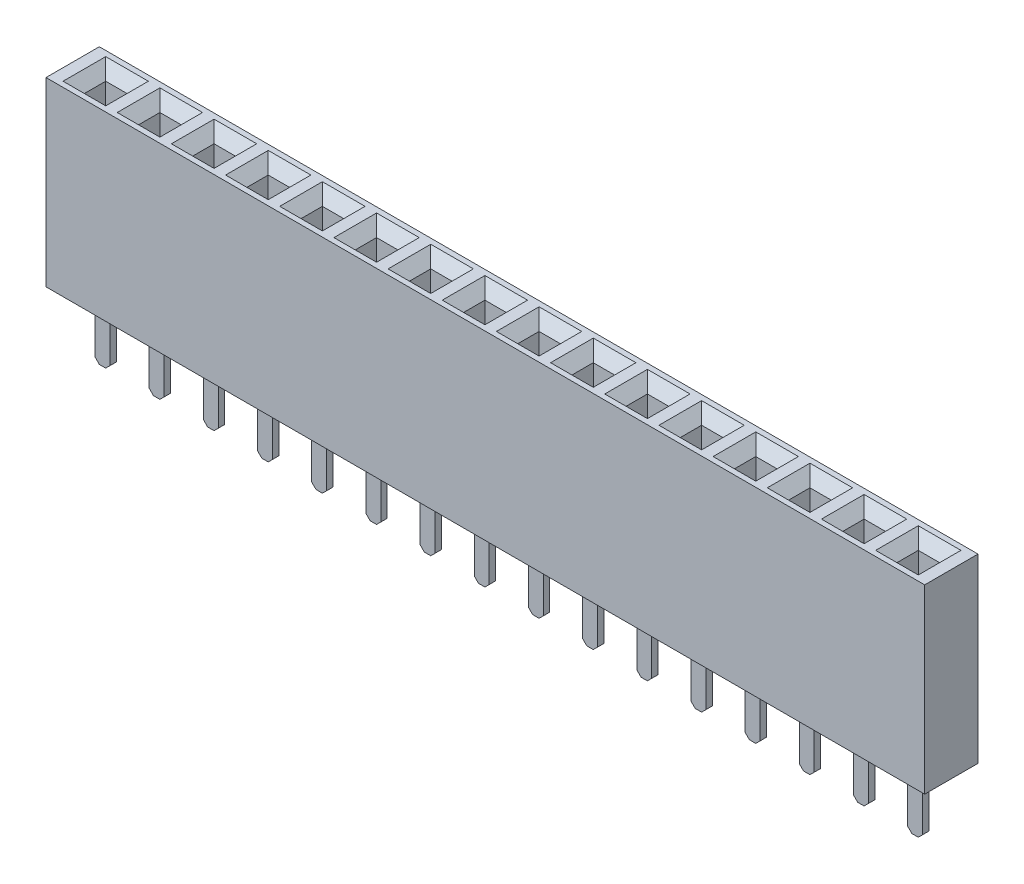
SolidWorks part; units mm, degrees
ref_plane "Спереди" through (0, 0, 0) normal (0, 0, 1) x (1, 0, 0)
ref_plane "Сверху" through (0, 0, 0) normal (0, 1, 0) x (1, 0, 0)
ref_plane "Справа" through (0, 0, 0) normal (1, 0, 0) x (0, 0, -1)
sketch "Эскиз1" plane through (0, 0, 0) normal (0, 1, 0) x (1, 0, 0)
  line L1 (-20.6, -1.25) -> (20.6, -1.25)
  line L2 (-20.6, -1.25) -> (-20.6, 1.25)
  line L3 (-20.6, 1.25) -> (20.6, 1.25)
  line L4 (20.6, -1.25) -> (20.6, 1.25)
  line L5 (-20.6, -1.25) -> (20.6, 1.25) construction
  line L6 (-20.6, 1.25) -> (20.6, -1.25) construction
  point P0 (0, 0)
  dimension "D1" = 41.2
  dimension "D2" = 2.5
extrude "Бобышка-Вытянуть1" add sketch "Эскиз1" along normal blind 8.5
sketch "Эскиз2" plane through (0, 8.5, 0) normal (0, 1, 0) x (1, 0, 0)
  line L0 (-17.01, 0.5) -> (-16.01, 0.5)
  line L1 (-19.55, 0.5) -> (-18.55, 0.5)
  line L2 (-19.55, 0.5) -> (-19.55, -0.5)
  line L3 (-19.55, -0.5) -> (-18.55, -0.5)
  line L4 (-18.55, 0.5) -> (-18.55, -0.5)
  line L5 (-19.55, 0.5) -> (-18.55, -0.5) construction
  line L6 (-19.55, -0.5) -> (-18.55, 0.5) construction
  line L7 (-17.01, 0.5) -> (-17.01, -0.5)
  line L8 (-17.01, -0.5) -> (-16.01, -0.5)
  line L9 (-16.01, 0.5) -> (-16.01, -0.5)
  line L10 (-17.01, 0.5) -> (-16.01, -0.5) construction
  line L11 (-17.01, -0.5) -> (-16.01, 0.5) construction
  line L12 (-14.47, 0.5) -> (-13.47, 0.5)
  line L13 (-14.47, 0.5) -> (-14.47, -0.5)
  line L14 (-14.47, -0.5) -> (-13.47, -0.5)
  line L15 (-13.47, 0.5) -> (-13.47, -0.5)
  line L16 (-14.47, 0.5) -> (-13.47, -0.5) construction
  line L17 (-14.47, -0.5) -> (-13.47, 0.5) construction
  line L18 (-11.93, 0.5) -> (-10.93, 0.5)
  line L19 (-11.93, 0.5) -> (-11.93, -0.5)
  line L20 (-11.93, -0.5) -> (-10.93, -0.5)
  line L21 (-10.93, 0.5) -> (-10.93, -0.5)
  line L22 (-11.93, 0.5) -> (-10.93, -0.5) construction
  line L23 (-11.93, -0.5) -> (-10.93, 0.5) construction
  line L24 (-9.39, 0.5) -> (-8.39, 0.5)
  line L25 (-9.39, 0.5) -> (-9.39, -0.5)
  line L26 (-9.39, -0.5) -> (-8.39, -0.5)
  line L27 (-8.39, 0.5) -> (-8.39, -0.5)
  line L28 (-9.39, 0.5) -> (-8.39, -0.5) construction
  line L29 (-9.39, -0.5) -> (-8.39, 0.5) construction
  line L30 (-6.85, 0.5) -> (-5.85, 0.5)
  line L31 (-6.85, 0.5) -> (-6.85, -0.5)
  line L32 (-6.85, -0.5) -> (-5.85, -0.5)
  line L33 (-5.85, 0.5) -> (-5.85, -0.5)
  line L34 (-6.85, 0.5) -> (-5.85, -0.5) construction
  line L35 (-6.85, -0.5) -> (-5.85, 0.5) construction
  line L36 (-4.31, 0.5) -> (-3.31, 0.5)
  line L37 (-4.31, 0.5) -> (-4.31, -0.5)
  line L38 (-4.31, -0.5) -> (-3.31, -0.5)
  line L39 (-3.31, 0.5) -> (-3.31, -0.5)
  line L40 (-4.31, 0.5) -> (-3.31, -0.5) construction
  line L41 (-4.31, -0.5) -> (-3.31, 0.5) construction
  line L42 (-1.77, 0.5) -> (-0.77, 0.5)
  line L43 (-1.77, 0.5) -> (-1.77, -0.5)
  line L44 (-1.77, -0.5) -> (-0.77, -0.5)
  line L45 (-0.77, 0.5) -> (-0.77, -0.5)
  line L46 (-1.77, 0.5) -> (-0.77, -0.5) construction
  line L47 (-1.77, -0.5) -> (-0.77, 0.5) construction
  line L48 (0.77, 0.5) -> (1.77, 0.5)
  line L49 (0.77, 0.5) -> (0.77, -0.5)
  line L50 (0.77, -0.5) -> (1.77, -0.5)
  line L51 (1.77, 0.5) -> (1.77, -0.5)
  line L52 (0.77, 0.5) -> (1.77, -0.5) construction
  line L53 (0.77, -0.5) -> (1.77, 0.5) construction
  line L54 (3.31, 0.5) -> (4.31, 0.5)
  line L55 (3.31, 0.5) -> (3.31, -0.5)
  line L56 (3.31, -0.5) -> (4.31, -0.5)
  line L57 (4.31, 0.5) -> (4.31, -0.5)
  line L58 (3.31, 0.5) -> (4.31, -0.5) construction
  line L59 (3.31, -0.5) -> (4.31, 0.5) construction
  line L60 (5.85, 0.5) -> (6.85, 0.5)
  line L61 (5.85, 0.5) -> (5.85, -0.5)
  line L62 (5.85, -0.5) -> (6.85, -0.5)
  line L63 (6.85, 0.5) -> (6.85, -0.5)
  line L64 (5.85, 0.5) -> (6.85, -0.5) construction
  line L65 (5.85, -0.5) -> (6.85, 0.5) construction
  line L66 (8.39, 0.5) -> (9.39, 0.5)
  line L67 (8.39, 0.5) -> (8.39, -0.5)
  line L68 (8.39, -0.5) -> (9.39, -0.5)
  line L69 (9.39, 0.5) -> (9.39, -0.5)
  line L70 (8.39, 0.5) -> (9.39, -0.5) construction
  line L71 (8.39, -0.5) -> (9.39, 0.5) construction
  line L72 (10.93, 0.5) -> (11.93, 0.5)
  line L73 (10.93, 0.5) -> (10.93, -0.5)
  line L74 (10.93, -0.5) -> (11.93, -0.5)
  line L75 (11.93, 0.5) -> (11.93, -0.5)
  line L76 (10.93, 0.5) -> (11.93, -0.5) construction
  line L77 (10.93, -0.5) -> (11.93, 0.5) construction
  line L78 (13.47, 0.5) -> (14.47, 0.5)
  line L79 (13.47, 0.5) -> (13.47, -0.5)
  line L80 (13.47, -0.5) -> (14.47, -0.5)
  line L81 (14.47, 0.5) -> (14.47, -0.5)
  line L82 (13.47, 0.5) -> (14.47, -0.5) construction
  line L83 (13.47, -0.5) -> (14.47, 0.5) construction
  line L84 (16.01, 0.5) -> (17.01, 0.5)
  line L85 (16.01, 0.5) -> (16.01, -0.5)
  line L86 (16.01, -0.5) -> (17.01, -0.5)
  line L87 (17.01, 0.5) -> (17.01, -0.5)
  line L88 (16.01, 0.5) -> (17.01, -0.5) construction
  line L89 (16.01, -0.5) -> (17.01, 0.5) construction
  line L90 (18.55, 0.5) -> (19.55, 0.5)
  line L91 (18.55, 0.5) -> (18.55, -0.5)
  line L92 (18.55, -0.5) -> (19.55, -0.5)
  line L93 (19.55, 0.5) -> (19.55, -0.5)
  line L94 (18.55, 0.5) -> (19.55, -0.5) construction
  line L95 (18.55, -0.5) -> (19.55, 0.5) construction
  line L96 (-1.27, 0) -> (1.27, 0) construction
  point P0 (-19.05, 0)
  point P5 (-16.51, 0)
  point P12 (-13.97, 0)
  point P17 (-11.43, 0)
  point P22 (-8.89, 0)
  point P27 (-6.35, 0)
  point P32 (-3.81, 0)
  point P37 (-1.27, 0)
  point P42 (1.27, 0)
  point P47 (3.81, 0)
  point P52 (6.35, 0)
  point P57 (8.89, 0)
  point P62 (11.43, 0)
  point P67 (13.97, 0)
  point P72 (16.51, 0)
  point P77 (19.05, 0)
  point P83 (0, 0)
  dimension "D1" = 1
  dimension "D3" = 2.54
  dimension "D2" = 16
extrude "Вырез-Вытянуть1" cut sketch "Эскиз2" against normal blind 7
chamfer "Фаска2" distance 0.5 angle 45 64 edges at (-19.05, 8.5, 0.5) (-18.55, 8.5, 0) (-19.55, 8.5, 0) (-19.05, 8.5, -0.5) (18.55, 8.5, 0) (19.05, 8.5, 0.5) (19.55, 8.5, 0) (19.05, 8.5, -0.5) (16.01, 8.5, 0) (16.51, 8.5, 0.5) (17.01, 8.5, 0) (16.51, 8.5, -0.5) (13.47, 8.5, 0) (13.97, 8.5, 0.5) (14.47, 8.5, 0) (13.97, 8.5, -0.5) (10.93, 8.5, 0) (11.43, 8.5, 0.5) (11.93, 8.5, 0) (11.43, 8.5, -0.5) (8.39, 8.5, 0) (8.89, 8.5, 0.5) (9.39, 8.5, 0) (8.89, 8.5, -0.5) (5.85, 8.5, 0) (6.35, 8.5, 0.5) (6.85, 8.5, 0) (6.35, 8.5, -0.5) (3.31, 8.5, 0) (3.81, 8.5, 0.5) (4.31, 8.5, 0) (3.81, 8.5, -0.5) (0.77, 8.5, 0) (1.27, 8.5, 0.5) (1.77, 8.5, 0) (1.27, 8.5, -0.5) (-1.77, 8.5, 0) (-1.27, 8.5, 0.5) (-0.77, 8.5, 0) (-1.27, 8.5, -0.5) (-4.31, 8.5, 0) (-3.81, 8.5, 0.5) (-3.31, 8.5, 0) (-3.81, 8.5, -0.5) (-6.85, 8.5, 0) (-6.35, 8.5, 0.5) (-5.85, 8.5, 0) (-6.35, 8.5, -0.5) (-9.39, 8.5, 0) (-8.89, 8.5, 0.5) (-8.39, 8.5, 0) (-8.89, 8.5, -0.5) (-11.93, 8.5, 0) (-11.43, 8.5, 0.5) (-10.93, 8.5, 0) (-11.43, 8.5, -0.5) (-14.47, 8.5, 0) (-13.97, 8.5, 0.5) (-13.47, 8.5, 0) (-13.97, 8.5, -0.5) (-17.01, 8.5, 0) (-16.51, 8.5, 0.5) (-16.01, 8.5, 0) (-16.51, 8.5, -0.5)
sketch "Эскиз3" plane through (0, 0, 0) normal (0, -1, 0) x (1, 0, 0)
  line L0 (16.86, 0.15) -> (16.16, 0.15)
  line L1 (19.4, 0.15) -> (18.7, 0.15)
  line L2 (19.4, 0.15) -> (19.4, -0.15)
  line L3 (19.4, -0.15) -> (18.7, -0.15)
  line L4 (18.7, 0.15) -> (18.7, -0.15)
  line L5 (19.4, 0.15) -> (18.7, -0.15) construction
  line L6 (19.4, -0.15) -> (18.7, 0.15) construction
  line L7 (16.86, 0.15) -> (16.86, -0.15)
  line L8 (16.86, -0.15) -> (16.16, -0.15)
  line L9 (16.16, 0.15) -> (16.16, -0.15)
  line L10 (16.86, 0.15) -> (16.16, -0.15) construction
  line L11 (16.86, -0.15) -> (16.16, 0.15) construction
  line L12 (14.32, 0.15) -> (13.62, 0.15)
  line L13 (14.32, 0.15) -> (14.32, -0.15)
  line L14 (14.32, -0.15) -> (13.62, -0.15)
  line L15 (13.62, 0.15) -> (13.62, -0.15)
  line L16 (14.32, 0.15) -> (13.62, -0.15) construction
  line L17 (14.32, -0.15) -> (13.62, 0.15) construction
  line L18 (11.78, 0.15) -> (11.08, 0.15)
  line L19 (11.78, 0.15) -> (11.78, -0.15)
  line L20 (11.78, -0.15) -> (11.08, -0.15)
  line L21 (11.08, 0.15) -> (11.08, -0.15)
  line L22 (11.78, 0.15) -> (11.08, -0.15) construction
  line L23 (11.78, -0.15) -> (11.08, 0.15) construction
  line L24 (9.24, 0.15) -> (8.54, 0.15)
  line L25 (9.24, 0.15) -> (9.24, -0.15)
  line L26 (9.24, -0.15) -> (8.54, -0.15)
  line L27 (8.54, 0.15) -> (8.54, -0.15)
  line L28 (9.24, 0.15) -> (8.54, -0.15) construction
  line L29 (9.24, -0.15) -> (8.54, 0.15) construction
  line L30 (6.7, 0.15) -> (6, 0.15)
  line L31 (6.7, 0.15) -> (6.7, -0.15)
  line L32 (6.7, -0.15) -> (6, -0.15)
  line L33 (6, 0.15) -> (6, -0.15)
  line L34 (6.7, 0.15) -> (6, -0.15) construction
  line L35 (6.7, -0.15) -> (6, 0.15) construction
  line L36 (4.16, 0.15) -> (3.46, 0.15)
  line L37 (4.16, 0.15) -> (4.16, -0.15)
  line L38 (4.16, -0.15) -> (3.46, -0.15)
  line L39 (3.46, 0.15) -> (3.46, -0.15)
  line L40 (4.16, 0.15) -> (3.46, -0.15) construction
  line L41 (4.16, -0.15) -> (3.46, 0.15) construction
  line L42 (1.62, 0.15) -> (0.92, 0.15)
  line L43 (1.62, 0.15) -> (1.62, -0.15)
  line L44 (1.62, -0.15) -> (0.92, -0.15)
  line L45 (0.92, 0.15) -> (0.92, -0.15)
  line L46 (1.62, 0.15) -> (0.92, -0.15) construction
  line L47 (1.62, -0.15) -> (0.92, 0.15) construction
  line L48 (-0.92, 0.15) -> (-1.62, 0.15)
  line L49 (-0.92, 0.15) -> (-0.92, -0.15)
  line L50 (-0.92, -0.15) -> (-1.62, -0.15)
  line L51 (-1.62, 0.15) -> (-1.62, -0.15)
  line L52 (-0.92, 0.15) -> (-1.62, -0.15) construction
  line L53 (-0.92, -0.15) -> (-1.62, 0.15) construction
  line L54 (-3.46, 0.15) -> (-4.16, 0.15)
  line L55 (-3.46, 0.15) -> (-3.46, -0.15)
  line L56 (-3.46, -0.15) -> (-4.16, -0.15)
  line L57 (-4.16, 0.15) -> (-4.16, -0.15)
  line L58 (-3.46, 0.15) -> (-4.16, -0.15) construction
  line L59 (-3.46, -0.15) -> (-4.16, 0.15) construction
  line L60 (-6, 0.15) -> (-6.7, 0.15)
  line L61 (-6, 0.15) -> (-6, -0.15)
  line L62 (-6, -0.15) -> (-6.7, -0.15)
  line L63 (-6.7, 0.15) -> (-6.7, -0.15)
  line L64 (-6, 0.15) -> (-6.7, -0.15) construction
  line L65 (-6, -0.15) -> (-6.7, 0.15) construction
  line L66 (-8.54, 0.15) -> (-9.24, 0.15)
  line L67 (-8.54, 0.15) -> (-8.54, -0.15)
  line L68 (-8.54, -0.15) -> (-9.24, -0.15)
  line L69 (-9.24, 0.15) -> (-9.24, -0.15)
  line L70 (-8.54, 0.15) -> (-9.24, -0.15) construction
  line L71 (-8.54, -0.15) -> (-9.24, 0.15) construction
  line L72 (-11.08, 0.15) -> (-11.78, 0.15)
  line L73 (-11.08, 0.15) -> (-11.08, -0.15)
  line L74 (-11.08, -0.15) -> (-11.78, -0.15)
  line L75 (-11.78, 0.15) -> (-11.78, -0.15)
  line L76 (-11.08, 0.15) -> (-11.78, -0.15) construction
  line L77 (-11.08, -0.15) -> (-11.78, 0.15) construction
  line L78 (-13.62, 0.15) -> (-14.32, 0.15)
  line L79 (-13.62, 0.15) -> (-13.62, -0.15)
  line L80 (-13.62, -0.15) -> (-14.32, -0.15)
  line L81 (-14.32, 0.15) -> (-14.32, -0.15)
  line L82 (-13.62, 0.15) -> (-14.32, -0.15) construction
  line L83 (-13.62, -0.15) -> (-14.32, 0.15) construction
  line L84 (-16.16, 0.15) -> (-16.86, 0.15)
  line L85 (-16.16, 0.15) -> (-16.16, -0.15)
  line L86 (-16.16, -0.15) -> (-16.86, -0.15)
  line L87 (-16.86, 0.15) -> (-16.86, -0.15)
  line L88 (-16.16, 0.15) -> (-16.86, -0.15) construction
  line L89 (-16.16, -0.15) -> (-16.86, 0.15) construction
  line L90 (-18.7, 0.15) -> (-19.4, 0.15)
  line L91 (-18.7, 0.15) -> (-18.7, -0.15)
  line L92 (-18.7, -0.15) -> (-19.4, -0.15)
  line L93 (-19.4, 0.15) -> (-19.4, -0.15)
  line L94 (-18.7, 0.15) -> (-19.4, -0.15) construction
  line L95 (-18.7, -0.15) -> (-19.4, 0.15) construction
  line L96 (1.27, 0) -> (-1.27, 0) construction
  point P0 (19.05, 0)
  point P5 (16.51, 0)
  point P12 (13.97, 0)
  point P17 (11.43, 0)
  point P22 (8.89, 0)
  point P27 (6.35, 0)
  point P32 (3.81, 0)
  point P37 (1.27, 0)
  point P42 (-1.27, 0)
  point P47 (-3.81, 0)
  point P52 (-6.35, 0)
  point P57 (-8.89, 0)
  point P62 (-11.43, 0)
  point P67 (-13.97, 0)
  point P72 (-16.51, 0)
  point P77 (-19.05, 0)
  dimension "D1" = 0.3
  dimension "D2" = 0.7
  dimension "D4" = 2.54
  dimension "D3" = 16
extrude "Бобышка-Вытянуть2" add sketch "Эскиз3" along normal blind 3
chamfer "Фаска3" distance 0.2 angle 45 32 edges at (18.7, -3, 0) (19.4, -3, 0) (-19.4, -3, 0) (-18.7, -3, 0) (-16.86, -3, 0) (-16.16, -3, 0) (-14.32, -3, 0) (-13.62, -3, 0) (-11.78, -3, 0) (-11.08, -3, 0) (-9.24, -3, 0) (-8.54, -3, 0) (-6.7, -3, 0) (-6, -3, 0) (-4.16, -3, 0) (-3.46, -3, 0) (-1.62, -3, 0) (-0.92, -3, 0) (0.92, -3, 0) (1.62, -3, 0) (3.46, -3, 0) (4.16, -3, 0) (6, -3, 0) (6.7, -3, 0) (8.54, -3, 0) (9.24, -3, 0) (11.08, -3, 0) (11.78, -3, 0) (13.62, -3, 0) (14.32, -3, 0) (16.16, -3, 0) (16.86, -3, 0)
